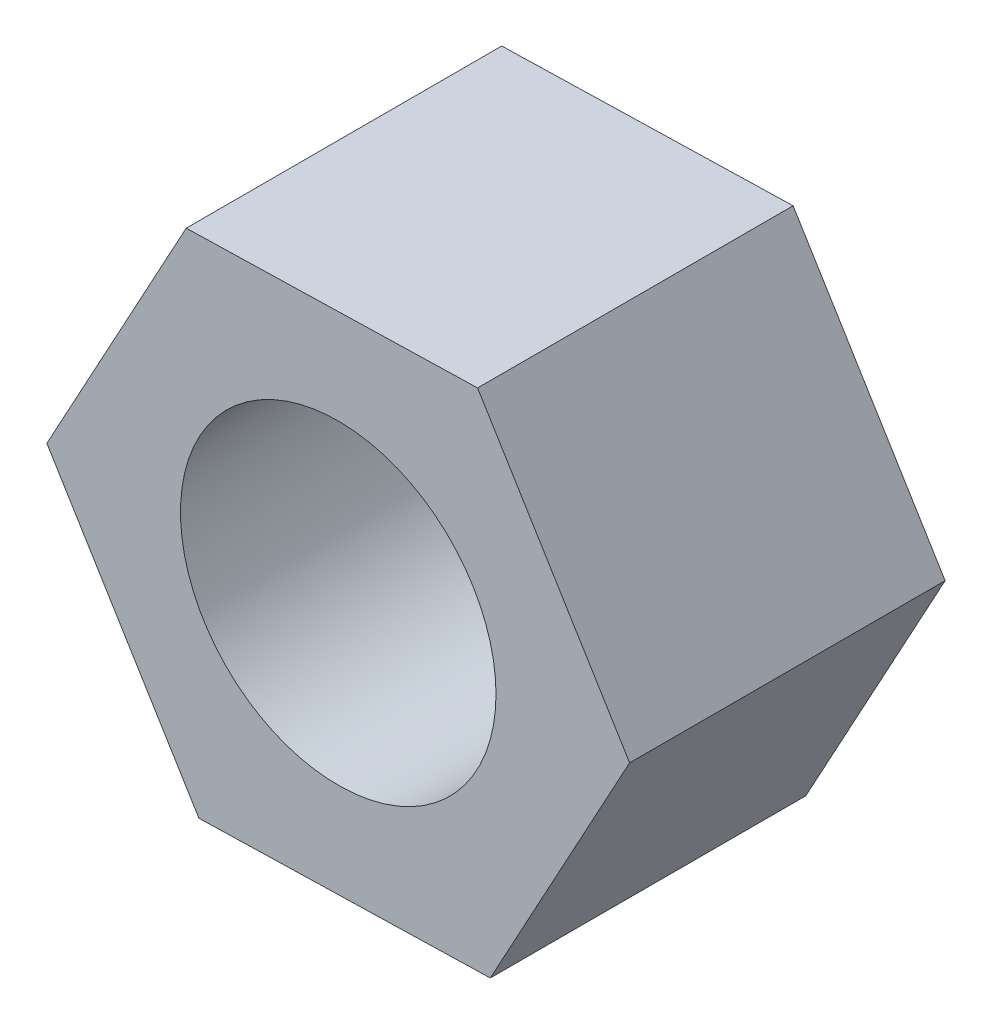
SolidWorks part; units mm, degrees
ref_plane "Front Plane" through (0, 0, 0) normal (1, 0, 0) x (0, 1, 0)
ref_plane "Top Plane" through (0, 0, 0) normal (0, 0, 1) x (0, 1, 0)
ref_plane "Right Plane" through (0, 0, 0) normal (0, 1, 0) x (-1, 0, 0)
sketch "Sketch1" plane through (0, 0, 0) normal (0, 0, 1) x (0, 1, 0)
  line L1 (4.0567, -2.2082) -> (3.9407, 2.4091)
  line L2 (3.9407, 2.4091) -> (-0.116, 4.6173)
  line L3 (-0.116, 4.6173) -> (-4.0567, 2.2082)
  line L4 (-4.0567, 2.2082) -> (-3.9407, -2.4091)
  line L5 (-3.9407, -2.4091) -> (0.116, -4.6173)
  line L6 (0.116, -4.6173) -> (4.0567, -2.2082)
  circle A0 centre (0, 0) radius 4 construction
  dimension "D1" = 8
extrude "Boss-Extrude2" add sketch "Sketch1" along normal blind 5
sketch "Sketch3" plane through (0, 0, 5) normal (0, 0, 1) x (1, 0, 0)
  circle A0 centre (0, 0) radius 2.5
  dimension "D1" = 5
extrude "Cut-Extrude1" cut sketch "Sketch3" against normal mid plane 18
